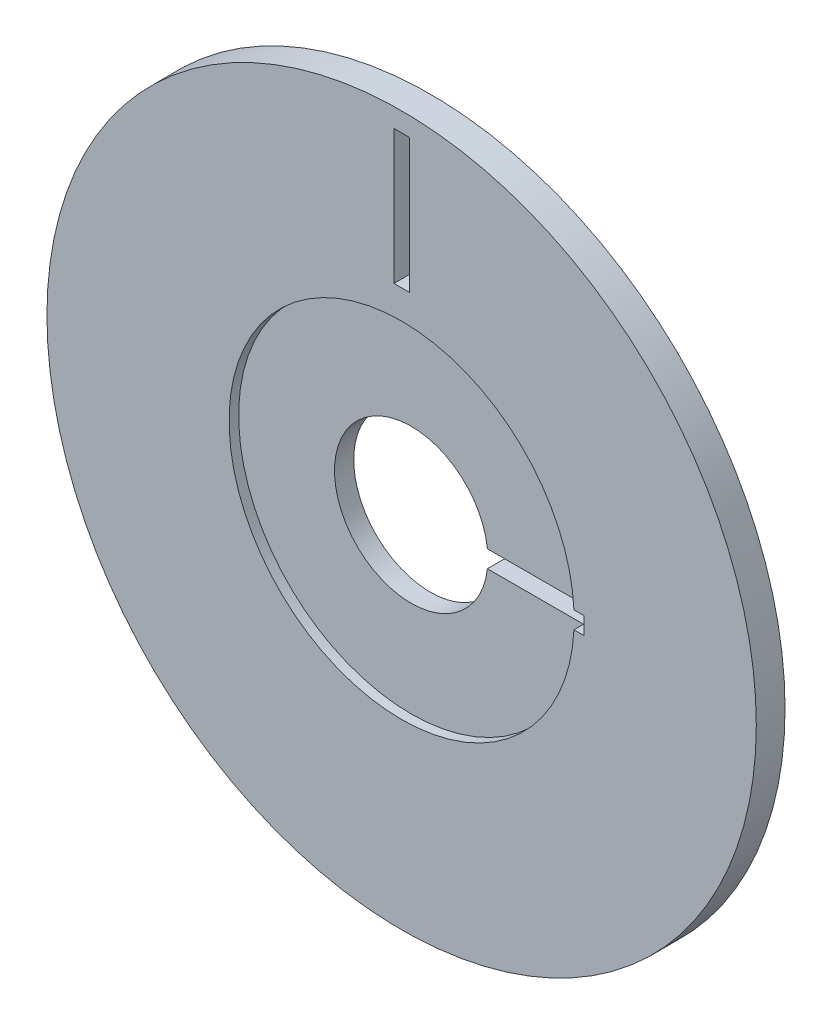
SolidWorks part; units mm, degrees
ref_plane "Спереди" through (0, 0, 0) normal (0, 0, 1) x (1, 0, 0)
ref_plane "Сверху" through (0, 0, 0) normal (0, 1, 0) x (1, 0, 0)
ref_plane "Справа" through (0, 0, 0) normal (1, 0, 0) x (0, 0, -1)
sketch "Эскиз1" plane through (0, 0, 0) normal (0, 0, 1) x (1, 0, 0)
  circle A0 centre (0, 0) radius 18.5
  dimension "D1" = 37
extrude "Бобышка-Вытянуть1" add sketch "Эскиз1" along normal blind 1.5
sketch "Эскиз2" plane through (0, 0, 1.5) normal (0, 0, 1) x (1, 0, 0)
  circle A0 centre (0, 0) radius 4
  dimension "D1" = 8
extrude "Вырез-Вытянуть1" cut sketch "Эскиз2" against normal through all
sketch "Эскиз3" plane through (0, 0, 1.5) normal (0, 0, 1) x (1, 0, 0)
  circle A0 centre (0, 0) radius 9
  dimension "D1" = 18
extrude "Вырез-Вытянуть2" cut sketch "Эскиз3" against normal blind 0.5
sketch "Эскиз4" plane through (0, 0, 1.5) normal (0, 0, 1) x (1, 0, 0)
  line L1 (2.5134, 0.45) -> (9.5134, 0.45)
  line L2 (2.5134, 0.45) -> (2.5134, -0.45)
  line L3 (2.5134, -0.45) -> (9.5134, -0.45)
  line L4 (9.5134, 0.45) -> (9.5134, -0.45)
  point P4 (2.5134, 0)
  point P6 (9.5134, -0.45)
  dimension "D1" = 0
  dimension "D2" = 0.9
  dimension "D3" = 7
extrude "Вырез-Вытянуть3" cut sketch "Эскиз4" against normal through all
sketch "Эскиз5" plane through (0, 0, 1.5) normal (0, 0, 1) x (1, 0, 0)
  line L1 (-0.4, 17.5) -> (0.4, 17.5)
  line L2 (-0.4, 17.5) -> (-0.4, 10.5)
  line L3 (-0.4, 10.5) -> (0.4, 10.5)
  line L4 (0.4, 17.5) -> (0.4, 10.5)
  point P4 (0, 10.5)
  dimension "D1" = 0
  dimension "D2" = 0.8
  dimension "D3" = 17.5
  dimension "D4" = 7
extrude "Вырез-Вытянуть4" cut sketch "Эскиз5" against normal through all
